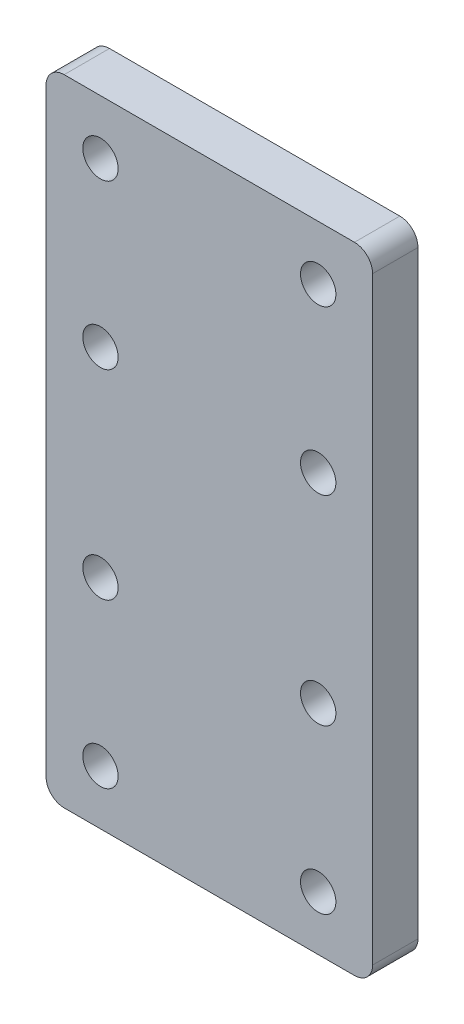
SolidWorks part; units mm, degrees
ref_plane "Front Plane" through (0, 0, 0) normal (0, 0, 1) x (1, 0, 0)
ref_plane "Top Plane" through (0, 0, 0) normal (0, 1, 0) x (1, 0, 0)
ref_plane "Right Plane" through (0, 0, 0) normal (1, 0, 0) x (0, 0, -1)
sketch "Sketch1" plane through (0, 0, 0) normal (0, 0, 1) x (1, 0, 0)
  line L0 (70, 132.7498) -> (70, -162.6372) construction
  line L1 (-90, 100) -> (-70, 100)
  line L2 (-100, 90) -> (-100, 29)
  line L3 (-90, -100) -> (-70, -100)
  line L4 (100, 90) -> (100, 29)
  line L5 (-100, 100) -> (100, -100) construction
  line L6 (-100, -100) -> (100, 100) construction
  line L7 (-70, 132.7498) -> (-70, -162.6372) construction
  line L8 (-121.9294, 0) -> (115.6873, 0) construction
  line L9 (-121.9294, 11) -> (127.292, 11) construction
  line L10 (-121.9294, -11) -> (111.2538, -11) construction
  line L11 (-58, 132.7498) -> (-58, -116.9522) construction
  line L12 (-82, 132.7498) -> (-82, -116.9522) construction
  line L13 (58, 116.0085) -> (58, -131.4445) construction
  line L14 (82, 116.0085) -> (82, -131.4445) construction
  line L15 (-121.9294, 29) -> (123.5119, 29) construction
  line L16 (-121.9294, -29) -> (123.5119, -29) construction
  line L17 (0, 85.0352) -> (0, -90) construction
  line L18 (6, 85.0352) -> (6, 65.1587) construction
  line L19 (-6, 85.0352) -> (-6, 65.1587) construction
  line L20 (-15.2579, 10) -> (13.899, 10) construction
  line L21 (-15.2579, -10) -> (14.5048, -10) construction
  line L22 (70, 100) -> (14.8842, 68.5052)
  line L23 (-14.8842, 68.5052) -> (-70, 100)
  line L24 (6, 29) -> (6, -90) construction
  line L25 (-6, 29) -> (-6, -90) construction
  line L26 (70, 100) -> (90, 100)
  line L27 (70, -100) -> (14.8842, -68.5052)
  line L28 (-14.8842, -68.5052) -> (-70, -100)
  line L29 (70, -100) -> (90, -100)
  line L30 (100, 29) -> (93.3723, 9.7797)
  line L31 (93.3723, -9.7797) -> (100, -29)
  line L32 (100, -29) -> (100, -90)
  line L33 (-100, 29) -> (-93.3723, 9.7797)
  line L34 (-93.3723, -9.7797) -> (-100, -29)
  line L35 (-100, -29) -> (-100, -90)
  circle A0 centre (-91.9239, 91.9239) radius 2
  circle A1 centre (91.9239, 91.9239) radius 2
  circle A2 centre (91.9239, -91.9239) radius 2
  circle A3 centre (-91.9239, -91.9239) radius 2
  arc A4 (100, 90) -> (90, 100) centre (90, 90) ccw
  arc A5 (90, -100) -> (100, -90) centre (90, -90) ccw
  arc A6 (-100, -90) -> (-90, -100) centre (-90, -90) ccw
  arc A7 (-100, 90) -> (-90, 100) centre (-90, 90) cw
  circle A8 centre (58, 29) radius 1.95
  circle A9 centre (82, 29) radius 1.95
  circle A10 centre (58, 11) radius 1.95
  circle A11 centre (82, 11) radius 1.95
  circle A12 centre (58, -11) radius 1.95
  circle A13 centre (58, -29) radius 1.95
  circle A14 centre (82, -11) radius 1.95
  circle A15 centre (82, -29) radius 1.95
  circle A16 centre (-82, 29) radius 1.95
  circle A17 centre (-58, 29) radius 1.95
  circle A18 centre (-82, 11) radius 1.95
  circle A19 centre (-58, 11) radius 1.95
  circle A20 centre (-82, -11) radius 1.95
  circle A21 centre (-82, -29) radius 1.95
  circle A22 centre (-58, -11) radius 1.95
  circle A23 centre (-58, -29) radius 1.95
  circle A24 centre (-6, 10) radius 1.5
  circle A25 centre (6, 10) radius 1.5
  circle A26 centre (-6, -10) radius 1.5
  circle A27 centre (6, -10) radius 1.5
  arc A28 (14.8842, 68.5052) -> (-14.8842, 68.5052) centre (0, 94.5525) cw
  arc A29 (14.8842, -68.5052) -> (-14.8842, -68.5052) centre (0, -94.5525) ccw
  arc A30 (93.3723, -9.7797) -> (93.3723, 9.7797) centre (121.7335, 0) cw
  arc A31 (-93.3723, -9.7797) -> (-93.3723, 9.7797) centre (-121.7335, 0) ccw
  point P0 (0, 0)
  point P103 (0, 60)
  point P118 (90, 0)
  dimension "D2" = 4
  dimension "D3" = 130
  dimension "D4" = 130
  dimension "D7" = 10
  dimension "D18" = 3.9
  dimension "D23" = 3
  dimension "D25" = 30
  dimension "D27" = 30
  dimension "D1" = 200
  dimension "D5" = 130
  dimension "D6" = 130
  dimension "D8" = 140
  dimension "D9" = 70
  dimension "D10" = 11
  dimension "D11" = 11
  dimension "D12" = 12
  dimension "D13" = 12
  dimension "D14" = 12
  dimension "D15" = 12
  dimension "D16" = 18
  dimension "D17" = 18
  dimension "D19" = 6
  dimension "D20" = 6
  dimension "D21" = 10
  dimension "D22" = 10
  dimension "D24" = 40
  dimension "D26" = 10
extrude "Boss-Extrude1" add sketch "Sketch1" along normal blind 5
sketch "Sketch2" plane through (0, 0, 5) normal (0, 0, 1) x (1, 0, 0)
  line L0 (0, 0) -> (-144.3314, 0) construction
  line L1 (-70, 41.4735) -> (-70, -45.1086) construction
  line L2 (-70, 100) -> (-90, 100) construction
  line L3 (-88, -35) -> (-52, -35)
  line L4 (-88, -35) -> (-88, 35)
  line L5 (-88, 35) -> (-52, 35)
  line L6 (-52, -35) -> (-52, 35)
  line L7 (-88, -35) -> (-52, 35) construction
  line L8 (-88, 35) -> (-52, -35) construction
  line L9 (-14.8842, 68.5052) -> (-70, 100) construction
  line L10 (70, 100) -> (14.8842, 68.5052) construction
  line L11 (90, 100) -> (70, 100) construction
  line L12 (100, 29) -> (100, 90) construction
  line L13 (93.3723, 9.7797) -> (100, 29) construction
  line L14 (100, -29) -> (93.3723, -9.7797) construction
  line L15 (100, -90) -> (100, -29) construction
  line L16 (-100, 90) -> (-100, 29) construction
  line L17 (70, -100) -> (90, -100) construction
  line L18 (-100, 29) -> (-93.3723, 9.7797) construction
  line L19 (-93.3723, -9.7797) -> (-100, -29) construction
  line L20 (-100, -29) -> (-100, -90) construction
  line L21 (-90, -100) -> (-70, -100) construction
  line L22 (-70, -100) -> (-14.8842, -68.5052) construction
  line L23 (14.8842, -68.5052) -> (70, -100) construction
  line L24 (14.8842, -68.5052) -> (70, -100)
  line L25 (-70, -100) -> (-14.8842, -68.5052)
  line L26 (-90, -100) -> (-70, -100)
  line L27 (-100, -29) -> (-100, -90)
  line L28 (-93.3723, -9.7797) -> (-100, -29)
  line L29 (-100, 29) -> (-93.3723, 9.7797)
  line L30 (-70, 100) -> (-90, 100)
  line L31 (-100, 90) -> (-100, 29)
  line L32 (100, -90) -> (100, -29)
  line L33 (100, -29) -> (93.3723, -9.7797)
  line L34 (93.3723, 9.7797) -> (100, 29)
  line L35 (100, 29) -> (100, 90)
  line L36 (90, 100) -> (70, 100)
  line L37 (70, 100) -> (14.8842, 68.5052)
  line L38 (-14.8842, 68.5052) -> (-70, 100)
  circle A2 centre (-58, -11) radius 1.95 construction
  circle A3 centre (-58, 29) radius 1.95 construction
  arc A5 (-14.8842, 68.5052) -> (14.8842, 68.5052) centre (0, 94.5525) ccw construction
  arc A6 (100, 90) -> (90, 100) centre (90, 90) ccw construction
  arc A7 (93.3723, 9.7797) -> (93.3723, -9.7797) centre (121.7335, 0) ccw construction
  arc A8 (-90, 100) -> (-100, 90) centre (-90, 90) ccw construction
  arc A9 (-93.3723, -9.7797) -> (-93.3723, 9.7797) centre (-121.7335, 0) ccw construction
  arc A10 (-100, -90) -> (-90, -100) centre (-90, -90) ccw construction
  arc A11 (14.8842, -68.5052) -> (-14.8842, -68.5052) centre (0, -94.5525) ccw construction
  arc A12 (90, -100) -> (100, -90) centre (90, -90) ccw construction
  arc A13 (90, -100) -> (100, -90) centre (90, -90) ccw
  arc A14 (14.8842, -68.5052) -> (-14.8842, -68.5052) centre (0, -94.5525) ccw
  arc A15 (-100, -90) -> (-90, -100) centre (-90, -90) ccw
  arc A16 (-93.3723, -9.7797) -> (-93.3723, 9.7797) centre (-121.7335, 0) ccw
  arc A17 (-90, 100) -> (-100, 90) centre (-90, 90) ccw
  arc A18 (93.3723, 9.7797) -> (93.3723, -9.7797) centre (121.7335, 0) ccw
  arc A19 (100, 90) -> (90, 100) centre (90, 90) ccw
  arc A20 (-14.8842, 68.5052) -> (14.8842, 68.5052) centre (0, 94.5525) ccw
  point P5 (-70, 0)
  point P18 (-80, 100)
  point P49 (80, -100)
  circle M7 centre (-6, 10) radius 1.5
  circle M13 centre (58, -11) radius 1.95
  circle M15 centre (58, 29) radius 1.95
  circle M17 centre (-91.9239, 91.9239) radius 2
  arc M18 (100, 90) -> (90, 100) centre (90, 90) ccw
  line M19 (90, 100) -> (70, 100)
  line M20 (70, 100) -> (14.8842, 68.5052)
  arc M21 (14.8842, 68.5052) -> (-14.8842, 68.5052) centre (0, 94.5525) cw
  line M22 (-14.8842, 68.5052) -> (-70, 100)
  line M23 (-70, 100) -> (-90, 100)
  arc M24 (-90, 100) -> (-100, 90) centre (-90, 90) ccw
  line M25 (-100, 90) -> (-100, 29)
  line M26 (-100, 29) -> (-93.3723, 9.7797)
  arc M27 (-93.3723, 9.7797) -> (-93.3723, -9.7797) centre (-121.7335, 0) cw
  line M28 (-93.3723, -9.7797) -> (-100, -29)
  line M29 (-100, -29) -> (-100, -90)
  arc M30 (-100, -90) -> (-90, -100) centre (-90, -90) ccw
  line M31 (-90, -100) -> (-70, -100)
  line M32 (-70, -100) -> (-14.8842, -68.5052)
  arc M33 (-14.8842, -68.5052) -> (14.8842, -68.5052) centre (0, -94.5525) cw
  line M34 (14.8842, -68.5052) -> (70, -100)
  line M35 (70, -100) -> (90, -100)
  arc M36 (90, -100) -> (100, -90) centre (90, -90) ccw
  line M37 (100, -90) -> (100, -29)
  line M38 (100, -29) -> (93.3723, -9.7797)
  arc M39 (93.3723, -9.7797) -> (93.3723, 9.7797) centre (121.7335, 0) cw
  line M40 (93.3723, 9.7797) -> (100, 29)
  line M41 (100, 29) -> (100, 90)
  circle M42 centre (91.9239, 91.9239) radius 2
  circle M44 centre (82, 29) radius 1.95
  circle M45 centre (82, 11) radius 1.95
  circle M46 centre (58, -29) radius 1.95
  circle M47 centre (82, -29) radius 1.95
  circle M52 centre (6, 10) radius 1.5
  circle M53 centre (6, -10) radius 1.5
  dimension "D1" = 12
  dimension "D2" = 6
  dimension "D3" = 6
extrude "Cut-Extrude1" cut sketch "Sketch2" against normal through all contours L6 L3 L4 L5 M41 M18 M19 M20 M21 M22 M23 M24 M25 M26 M27 M28 M29 M30 M31 M32 M33 M34 M35 M36 M37 M38 M39 M40 M7 M13 M15 M17 M42 M44 M46 M52 M53 M47 M45
fillet "Fillet1" radius 2 4 edges at (-52, -35, 2.5) (-88, -35, 2.5) (-88, 35, 2.5) (-52, 35, 2.5)
